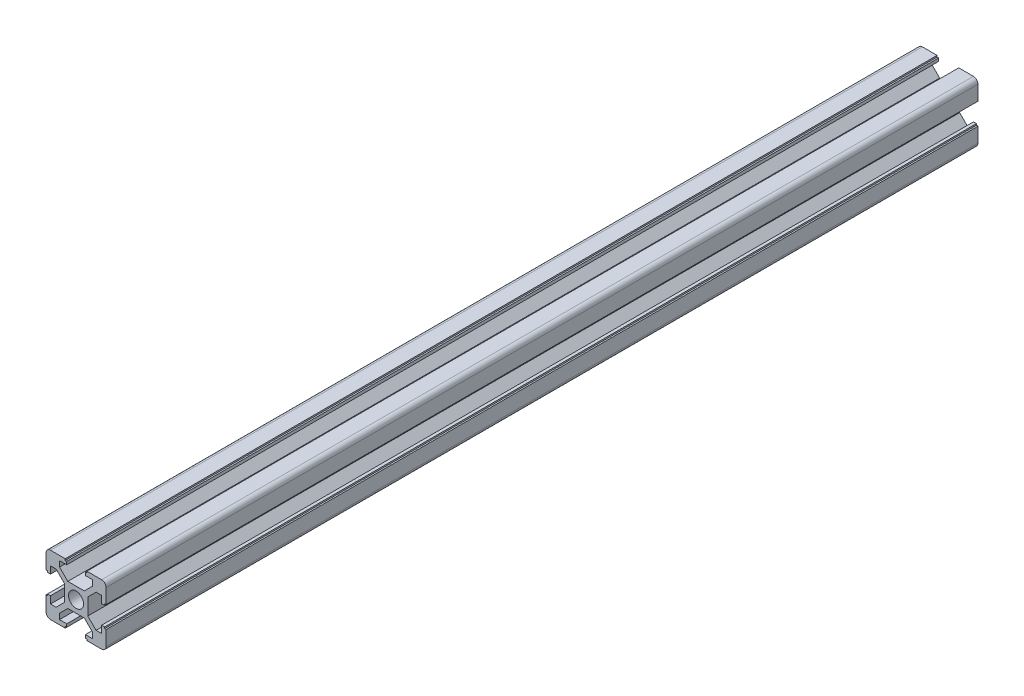
SolidWorks part; units mm, degrees
ref_plane "Plane1" through (0, 0, 0) normal (0, 0, 1) x (1, 0, 0)
ref_plane "Plane2" through (0, 0, 0) normal (0, 1, 0) x (1, 0, 0)
ref_plane "Plane3" through (0, 0, 0) normal (1, 0, 0) x (0, 0, -1)
sketch "Sketch1" plane through (0, 0, 0) normal (0, 0, 1) x (1, 0, 0)
  line L0 (-3.6, 10) -> (-3.6, 9.5)
  line L1 (-3.6, 9.5) -> (-3.1, 9.5)
  line L2 (-3.1, 9.5) -> (-3.1, 8.5)
  line L3 (-3.1, 8.5) -> (-5.5, 8.5)
  line L4 (-8.5, -10) -> (-3.6, -10)
  line L5 (-10, -8.5) -> (-10, -3.6)
  line L6 (8.5, 10) -> (3.6, 10)
  line L7 (10, 8.5) -> (10, 3.6)
  line L8 (0, 14.8756) -> (0, 0) construction
  line L9 (0, 0) -> (14.1675, 0) construction
  line L10 (-5.5, 8.5) -> (-5.5, 6.65)
  line L11 (-5.5, 6.65) -> (-2.75, 3.9)
  line L12 (-2.75, 3.9) -> (2.75, 3.9)
  line L13 (5.5, 6.65) -> (2.75, 3.9)
  line L14 (5.5, 8.5) -> (5.5, 6.65)
  line L15 (3.1, 8.5) -> (5.5, 8.5)
  line L16 (3.1, 9.5) -> (3.1, 8.5)
  line L17 (3.6, 9.5) -> (3.1, 9.5)
  line L18 (3.6, 10) -> (3.6, 9.5)
  line L19 (-3.6, 10) -> (-8.5, 10)
  line L20 (10, 3.6) -> (9.5, 3.6)
  line L21 (9.5, 3.6) -> (9.5, 3.1)
  line L22 (9.5, 3.1) -> (8.5, 3.1)
  line L23 (8.5, 3.1) -> (8.5, 5.5)
  line L24 (8.5, 5.5) -> (6.65, 5.5)
  line L25 (6.65, 5.5) -> (3.9, 2.75)
  line L26 (3.9, 2.75) -> (3.9, -2.75)
  line L27 (6.65, -5.5) -> (3.9, -2.75)
  line L28 (8.5, -5.5) -> (6.65, -5.5)
  line L29 (8.5, -3.1) -> (8.5, -5.5)
  line L30 (9.5, -3.1) -> (8.5, -3.1)
  line L31 (9.5, -3.6) -> (9.5, -3.1)
  line L32 (10, -3.6) -> (9.5, -3.6)
  line L33 (3.6, -10) -> (3.6, -9.5)
  line L34 (3.6, -9.5) -> (3.1, -9.5)
  line L35 (3.1, -9.5) -> (3.1, -8.5)
  line L36 (3.1, -8.5) -> (5.5, -8.5)
  line L37 (5.5, -8.5) -> (5.5, -6.65)
  line L38 (5.5, -6.65) -> (2.75, -3.9)
  line L39 (2.75, -3.9) -> (-2.75, -3.9)
  line L40 (-5.5, -6.65) -> (-2.75, -3.9)
  line L41 (-5.5, -8.5) -> (-5.5, -6.65)
  line L42 (-3.1, -8.5) -> (-5.5, -8.5)
  line L43 (-3.1, -9.5) -> (-3.1, -8.5)
  line L44 (-3.6, -9.5) -> (-3.1, -9.5)
  line L45 (-3.6, -10) -> (-3.6, -9.5)
  line L46 (-10, -3.6) -> (-9.5, -3.6)
  line L47 (-9.5, -3.6) -> (-9.5, -3.1)
  line L48 (-9.5, -3.1) -> (-8.5, -3.1)
  line L49 (-8.5, -3.1) -> (-8.5, -5.5)
  line L50 (-8.5, -5.5) -> (-6.65, -5.5)
  line L51 (-6.65, -5.5) -> (-3.9, -2.75)
  line L52 (-3.9, -2.75) -> (-3.9, 2.75)
  line L53 (-6.65, 5.5) -> (-3.9, 2.75)
  line L54 (-8.5, 5.5) -> (-6.65, 5.5)
  line L55 (-8.5, 3.1) -> (-8.5, 5.5)
  line L56 (-9.5, 3.1) -> (-8.5, 3.1)
  line L57 (-9.5, 3.6) -> (-9.5, 3.1)
  line L58 (-10, 3.6) -> (-9.5, 3.6)
  line L59 (3.6, -10) -> (8.5, -10)
  line L60 (-10, 3.6) -> (-10, 8.5)
  line L61 (10, -3.6) -> (10, -8.5)
  circle A0 centre (0, 0) radius 2.5
  arc A1 (-10, 8.5) -> (-8.5, 10) centre (-8.5, 8.5) cw
  arc A2 (10, 8.5) -> (8.5, 10) centre (8.5, 8.5) ccw
  arc A3 (-8.5, -10) -> (-10, -8.5) centre (-8.5, -8.5) cw
  arc A4 (8.5, -10) -> (10, -8.5) centre (8.5, -8.5) ccw
  point P0 (-10, 0)
  point P1 (10, 0)
  point P2 (0, 10)
  point P3 (0, -10)
  point P4 (0, 0)
  point P5 (-10, -10)
  point P6 (10, -10)
  point P7 (10, 10)
  point P8 (-10, 10)
  point P36 (-10, 10)
  point P39 (10, 10)
extrude "凸台-拉伸1" add sketch "Sketch1" along normal blind 290
